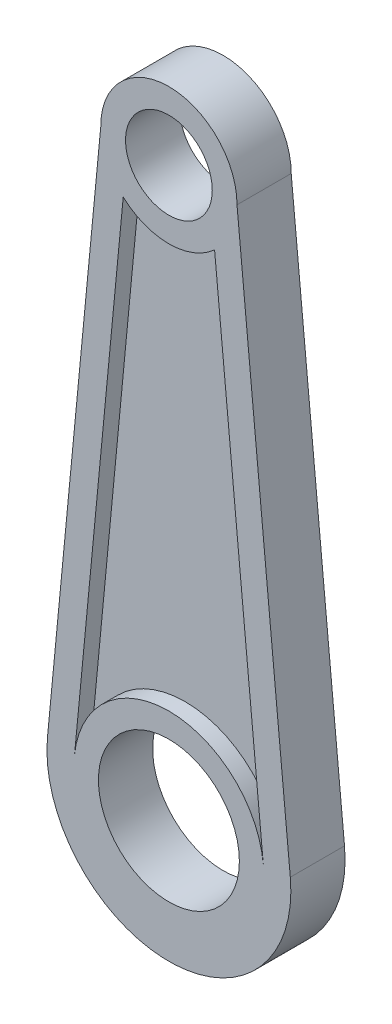
SolidWorks part; units mm, degrees
ref_plane "Front Plane" through (0, 0, 0) normal (0, 0, 1) x (1, 0, 0)
ref_plane "Top Plane" through (0, 0, 0) normal (0, 1, 0) x (1, 0, 0)
ref_plane "Right Plane" through (0, 0, 0) normal (1, 0, 0) x (0, 0, -1)
sketch "Sketch2" plane through (0, 0, 0) normal (0, 0, 1) x (1, 0, 0)
  line L0 (-12.4429, 105.8974) -> (-22.3971, 2.1489)
  line L1 (0, 125.4045) -> (0, -16.6989) construction
  line L2 (12.4429, 105.8974) -> (22.3971, 2.1489)
  arc A0 (-22.3971, 2.1489) -> (22.3971, 2.1489) centre (0, 0) ccw
  arc A1 (12.4429, 105.8974) -> (-12.4429, 105.8974) centre (0, 104.7036) ccw
  dimension "D1" = 45
  dimension "D2" = 25
extrude "Boss-Extrude1" add sketch "Sketch2" along normal blind 10
sketch "Sketch3" plane through (0, 0, 10) normal (0, 0, 1) x (1, 0, 0)
  line L4 (-7.4657, 105.4199) -> (-17.42, 1.6714)
  line L5 (17.42, 1.6714) -> (7.4657, 105.4199)
  line L6 (-7.4657, 105.4199) -> (-17.42, 1.6714)
  line L7 (17.42, 1.6714) -> (7.4657, 105.4199)
  arc A4 (7.4657, 105.4199) -> (-7.4657, 105.4199) centre (0, 104.7036) ccw
  arc A5 (-17.42, 1.6714) -> (17.42, 1.6714) centre (0, 0) ccw
  arc A6 (7.4657, 105.4199) -> (-7.4657, 105.4199) centre (0, 104.7036) ccw
  arc A7 (-17.42, 1.6714) -> (17.42, 1.6714) centre (0, 0) ccw
  dimension "D1" = 5
extrude "Cut-Extrude1" cut sketch "Sketch3" against normal blind 3
sketch "Sketch5" plane through (0, 0, 0) normal (0, 0, -1) x (-1, 0, 0)
  line L4 (-7.4657, 105.4199) -> (-17.42, 1.6714)
  line L5 (17.42, 1.6714) -> (7.4657, 105.4199)
  line L6 (-7.4657, 105.4199) -> (-17.42, 1.6714)
  line L7 (17.42, 1.6714) -> (7.4657, 105.4199)
  arc A4 (7.4657, 105.4199) -> (-7.4657, 105.4199) centre (0, 104.7036) ccw
  arc A5 (-17.42, 1.6714) -> (17.42, 1.6714) centre (0, 0) ccw
  arc A6 (7.4657, 105.4199) -> (-7.4657, 105.4199) centre (0, 104.7036) ccw
  arc A7 (-17.42, 1.6714) -> (17.42, 1.6714) centre (0, 0) ccw
  dimension "D1" = 5
extrude "Cut-Extrude2" cut sketch "Sketch5" against normal blind 3
sketch "Sketch8" plane through (0, 0, 0) normal (0, 0, 1) x (1, 0, 0)
  circle A0 centre (0, 0) radius 17.5
  circle A1 centre (0, 104.7036) radius 12.5625
extrude "Boss-Extrude3" add sketch "Sketch8" along normal through all
sketch "Sketch9" plane through (0, 0, 10) normal (0, 0, 1) x (1, 0, 0)
  circle A0 centre (0, 0) radius 13
  circle A1 centre (0, 104.7036) radius 8
  dimension "D1" = 26
  dimension "D2" = 16
extrude "Cut-Extrude4" cut sketch "Sketch9" against normal through all
